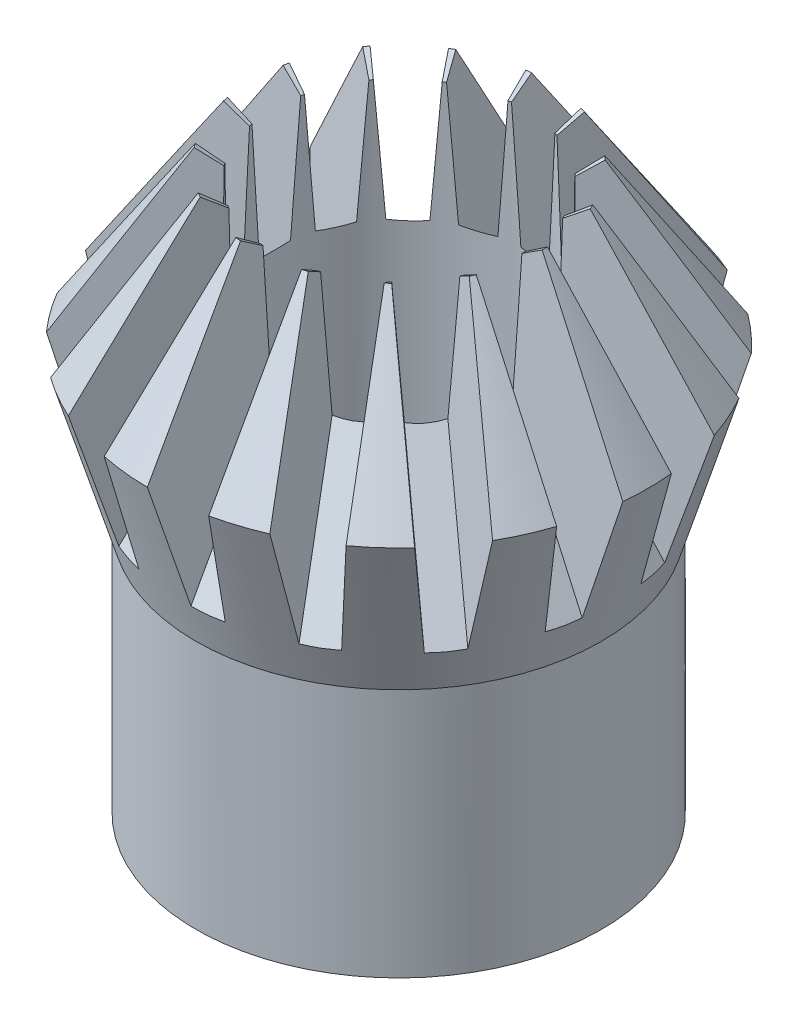
SolidWorks part; units mm, degrees
ref_plane "前视基准面" through (0, 0, 0) normal (0, 0, 1) x (1, 0, 0)
ref_plane "上视基准面" through (0, 0, 0) normal (0, 1, 0) x (1, 0, 0)
ref_plane "右视基准面" through (0, 0, 0) normal (1, 0, 0) x (0, 0, -1)
sketch "草图2" plane through (0, 0, 0) normal (1, 0, 0) x (0, 0, -1)
  line L0 (0, 0) -> (0, 18.3529) construction
  line L1 (4, 0) -> (6.5, 0)
  line L2 (6.5, 0) -> (6.5, 8)
  line L3 (6.5, 8) -> (8, 13)
  line L4 (8, 13) -> (4.6834, 18)
  line L5 (4.6834, 18) -> (4, 17.5467)
  line L6 (4, 17.5467) -> (4, 0)
  point P5 (6.5, 9.4709)
  dimension "D1" = 6.5
  dimension "D2" = 4
  dimension "D3" = 13
  dimension "D4" = 18
  dimension "D5" = 8
  dimension "D6" = 6
  dimension "D7" = 8
revolve "旋转1" add sketch "草图2" angle 360 about L0
ref_plane "基准面2" through (6.8605, 10.3426, 0) normal (0.5528, 0.8333, 0) x (0.8333, -0.5528, 0)
sketch "草图4" plane through (6.8605, 10.3426, 0) normal (0.5528, 0.8333, 0) x (0.8333, -0.5528, 0)
  line L0 (0, 0) -> (-17.7012, 0) construction
  line L1 (-10.8527, -0.5) -> (-10.8527, 0.5)
  line L2 (-10.8527, 0.5) -> (-13.8527, 0.9)
  line L3 (-13.8527, 0.9) -> (-13.8527, -0.9)
  line L4 (-10.8527, -0.5) -> (-13.8527, -0.9)
  ellipse E0 centre (-9.9499, 0) end of major axis (-9.9499, -4.6834) minor radius 3.9028 construction
  point P14 (-10.8527, 0)
  point P15 (-13.8527, 0)
  dimension "D1" = 0.9
  dimension "D2" = 0.5
  dimension "D3" = 3
extrude "切除-拉伸2" cut sketch "草图4" against normal up to next and the other way up to next
pattern_circular "阵列(圆周)1" count 15 over 360 about axis through (0, 0, 0) along (0, 1, 0) of "切除-拉伸2"
sketch "草图5" plane through (0, 0, 0) normal (0, 0, 1) x (1, 0, 0)
  line L0 (-6.5, 0) -> (6.5, 0) construction
  circle A0 centre (0, 4) radius 2
  dimension "D1" = 4
  dimension "D2" = 4
extrude "切除-拉伸3" cut sketch "草图5" against normal up to next
